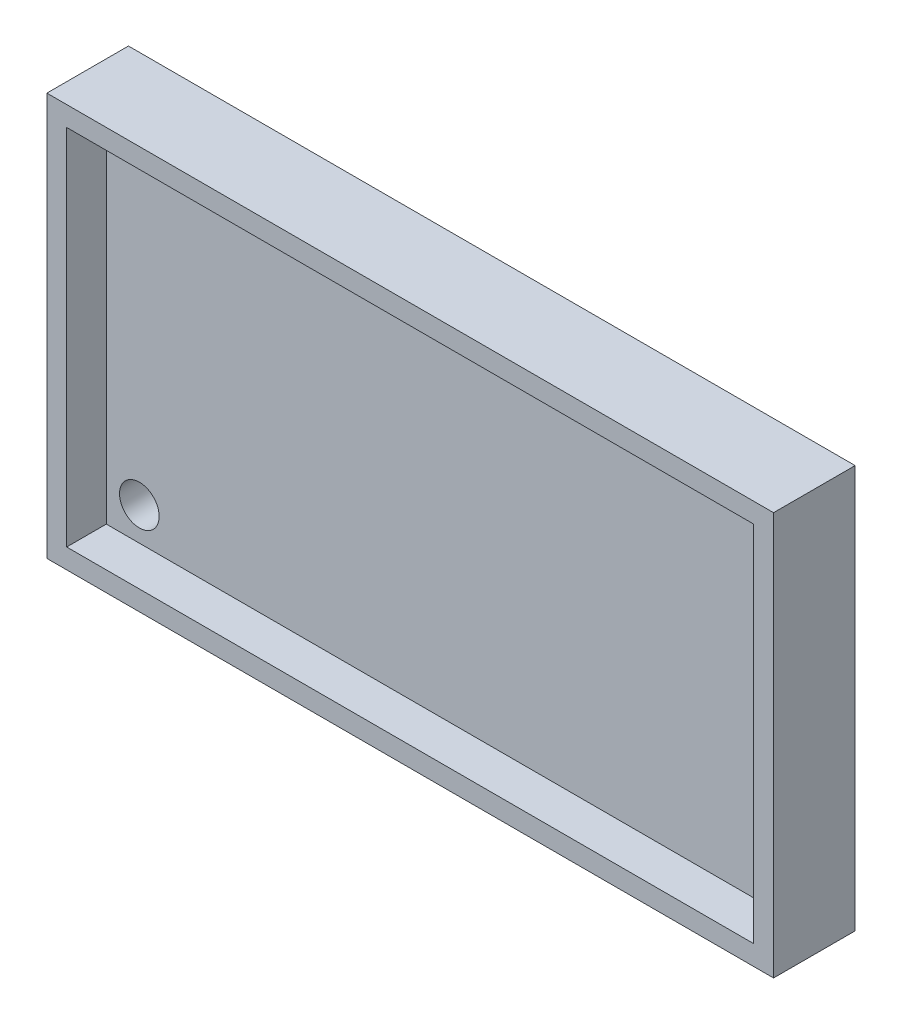
SolidWorks part; units mm, degrees
ref_plane "Front Plane" through (0, 0, 0) normal (0, 0, 1) x (1, 0, 0)
ref_plane "Top Plane" through (0, 0, 0) normal (0, 1, 0) x (1, 0, 0)
ref_plane "Right Plane" through (0, 0, 0) normal (1, 0, 0) x (0, 0, -1)
sketch "Sketch1" plane through (0, 0, 0) normal (0, 0, 1) x (1, 0, 0)
  line L1 (0, 0) -> (110, 0)
  line L2 (0, 0) -> (0, 61)
  line L3 (0, 61) -> (110, 61)
  line L4 (110, 0) -> (110, 61)
  dimension "D1" = 110
  dimension "D2" = 61
extrude "Boss-Extrude1" add sketch "Sketch1" along normal blind 6.35
sketch "Sketch3" plane through (0, 0, 6.35) normal (0, 0, 1) x (1, 0, 0)
  line L0 (0, 61) -> (0, 0) construction
  line L1 (3, 58) -> (107, 58)
  line L2 (3, 58) -> (3, 3)
  line L3 (3, 3) -> (107, 3)
  line L4 (107, 58) -> (107, 3)
  line L5 (110, 61) -> (0, 61) construction
  line L6 (0, 0) -> (110, 0) construction
  line L7 (110, 0) -> (110, 61) construction
  line L8 (0, 61) -> (0, 0)
  line L9 (0, 0) -> (110, 0)
  line L10 (110, 61) -> (110, 0)
  line L11 (0, 61) -> (110, 61)
  dimension "D1" = 3
  dimension "D2" = 3
  dimension "D3" = 3
  dimension "D4" = 3
extrude "Boss-Extrude2" add sketch "Sketch3" along normal blind 6
sketch "Sketch5" plane through (0, 0, 6.35) normal (0, 0, 1) x (1, 0, 0)
  line L0 (3, 3) -> (107, 3) construction
  line L1 (3, 58) -> (3, 3) construction
  circle A0 centre (8, 8) radius 3
  dimension "D1" = 5
  dimension "D3" = 6
  dimension "D2" = 5
extrude "Cut-Extrude1" cut sketch "Sketch5" against normal through all
